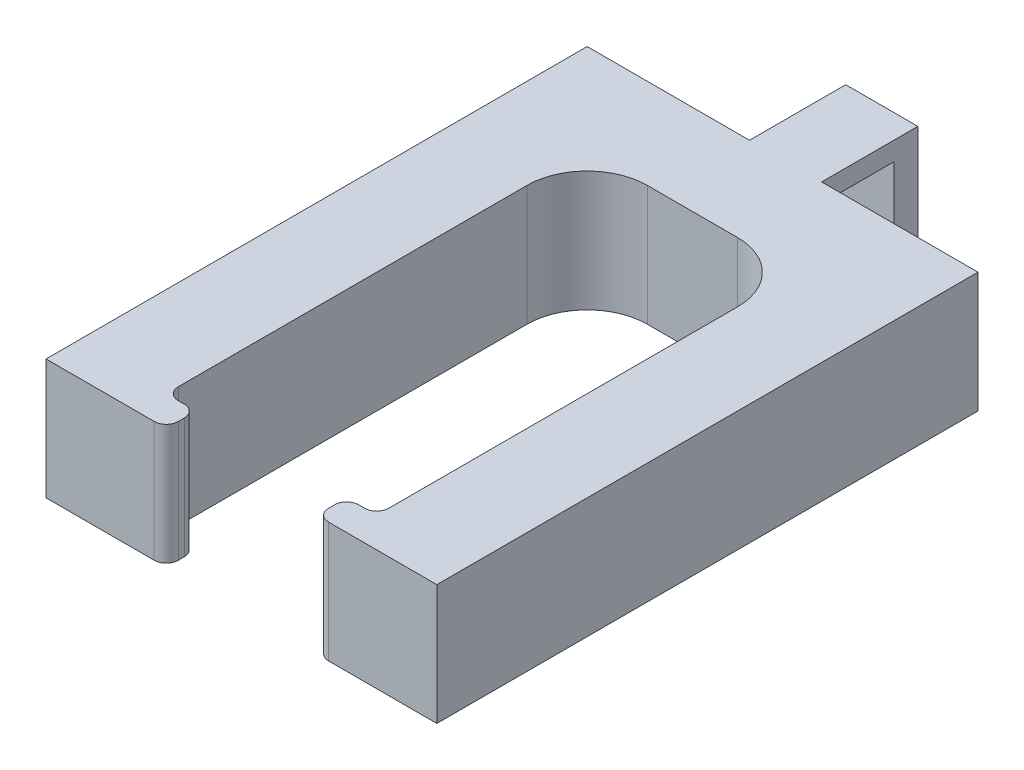
SolidWorks part; units mm, degrees
ref_plane "Спереди" through (0, 0, 0) normal (0, 0, 1) x (1, 0, 0)
ref_plane "Сверху" through (0, 0, 0) normal (0, 1, 0) x (1, 0, 0)
ref_plane "Справа" through (0, 0, 0) normal (1, 0, 0) x (0, 0, -1)
sketch "Эскиз4" plane through (0, 0, 0) normal (0, 1, 0) x (1, 0, 0)
  line L0 (0, 0) -> (0, 90)
  line L1 (0, 90) -> (65, 90)
  line L2 (65, 90) -> (65, 0)
  line L3 (0, 0) -> (18, 0)
  line L4 (20, 2) -> (20, 3)
  line L5 (18, 5) -> (17, 5)
  line L6 (15, 7) -> (15, 65)
  line L7 (25, 75) -> (40, 75)
  line L8 (50, 65) -> (50, 7)
  line L9 (48, 5) -> (47, 5)
  line L10 (45, 3) -> (45, 2)
  line L11 (47, 0) -> (65, 0)
  arc A0 (40, 75) -> (50, 65) centre (40, 65) cw
  arc A1 (15, 65) -> (25, 75) centre (25, 65) cw
  arc A2 (45, 2) -> (47, 0) centre (47, 2) ccw
  arc A3 (18, 0) -> (20, 2) centre (18, 2) ccw
  arc A4 (20, 3) -> (18, 5) centre (18, 3) ccw
  arc A5 (47, 5) -> (45, 3) centre (47, 3) ccw
  arc A6 (50, 7) -> (48, 5) centre (48, 7) cw
  arc A7 (17, 5) -> (15, 7) centre (17, 7) cw
  point P15 (50, 75)
  point P18 (15, 75)
  point P21 (45, 0)
  point P24 (20, 0)
  point P27 (20, 5)
  point P30 (45, 5)
  point P33 (50, 5)
  point P36 (15, 5)
  dimension "D11" = 10
  dimension "D12" = 2
  dimension "D1" = 90
  dimension "D2" = 65
  dimension "D3" = 20
  dimension "D4" = 20
  dimension "D5" = 5
  dimension "D6" = 5
  dimension "D7" = 70
  dimension "D8" = 35
  dimension "D9" = 70
  dimension "D10" = 15
extrude "Бобышка-Вытянуть1" add sketch "Эскиз4" along normal blind 20
ref_plane "Плоскость1" through (15, 0, -65) normal (0, 0, -1) x (-1, 0, 0)
sketch "Эскиз6" plane through (65, 0, 0) normal (1, 0, 0) x (0, 0, -1)
  line L1 (90, 20) -> (106, 20)
  line L2 (106, 20) -> (106, -20)
  line L3 (106, -20) -> (102, -20)
  line L4 (102, -20) -> (102, 16.8988)
  line L5 (102, 16.8988) -> (90, 16.8988)
  line L6 (90, 20) -> (90, 0) construction
  line L7 (90, 16.8988) -> (90, 20)
  dimension "D1" = 12
  dimension "D2" = 4
  dimension "D3" = 40
extrude "Бобышка-Вытянуть2" add sketch "Эскиз6" against normal blind 64
sketch "Эскиз7" plane through (0, 20, 0) normal (0, 1, 0) x (1, 0, 0)
  line L0 (27, 109.9448) -> (27, 90)
  line L1 (65, 90) -> (0, 90) construction
  line L2 (27, 90) -> (-10.9632, 90)
  line L3 (-10.9632, 90) -> (-10.9632, 111.7892)
  line L4 (-10.9632, 111.7892) -> (27, 109.9448)
  line L5 (39, 90) -> (39, 113.3262)
  line L6 (39, 90) -> (82.1889, 90)
  line L7 (82.1889, 90) -> (82.1889, 109.9448)
  line L8 (82.1889, 109.9448) -> (39, 113.3262)
  line L9 (1, 106) -> (65, 106) construction
  point P12 (33, 106)
  dimension "D1" = 12
  dimension "D2" = 6
  dimension "D3" = 12
extrude "Вырез-Вытянуть1" cut sketch "Эскиз7" against normal blind 64
